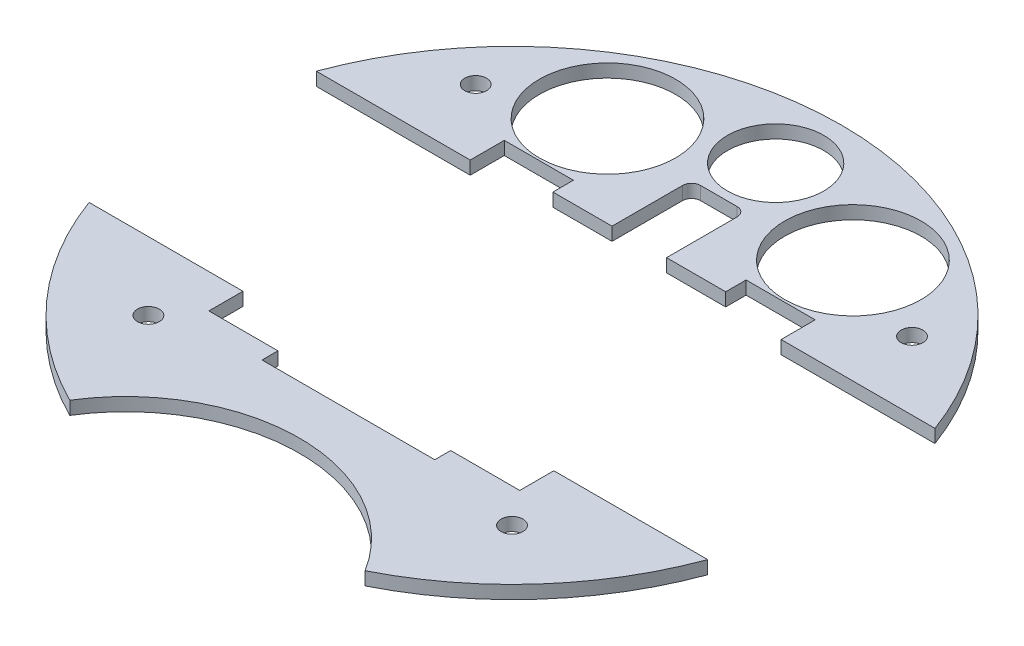
SolidWorks part; units mm, degrees
material "ABS"
ref_plane "Front Plane" through (0, 0, 0) normal (0, 0, 1) x (1, 0, 0)
ref_plane "Top Plane" through (0, 0, 0) normal (0, 1, 0) x (1, 0, 0)
ref_plane "Right Plane" through (0, 0, 0) normal (1, 0, 0) x (0, 0, -1)
sketch "Sketch1" plane through (0, 0, 0) normal (0, 1, 0) x (1, 0, 0)
  line L0 (0, -85) -> (-32.4891, -64.8129) construction
  line L1 (0, -85) -> (0, 0) construction
  arc A0 (32.4891, -64.8129) -> (-32.4891, -64.8129) centre (0, 0) ccw
  arc A1 (32.4891, -64.8129) -> (-32.4891, -64.8129) centre (0, -85) ccw
  dimension "D1" = 145
  dimension "D2" = 76.5
  dimension "D3" = 85
extrude "Boss-Extrude1" add sketch "Sketch1" along normal blind 2.9
sketch "solenoid placement" plane through (0, 2.9, 0) normal (0, 1, 0) x (1, 0, 0)
  line L4 (-19, -36) -> (19, -36)
  line L5 (-19, 28) -> (-19, -36)
  line L10 (19, 28) -> (-19, 28)
  line L11 (19, -36) -> (19, 28)
  line L12 (-19, -36) -> (19, -36)
  line L13 (-19, 28) -> (-19, -36)
  line L14 (19, 28) -> (-19, 28)
  line L15 (19, -36) -> (19, 28)
  dimension "D1" = 0
extrude "Cut-Extrude1" cut sketch "solenoid placement" against normal through all
sketch "Sketch7" plane through (0, 2.9, 0) normal (0, 1, 0) x (1, 0, 0)
  circle A3 centre (27, 48) radius 15
  circle A4 centre (27, 48) radius 15
  circle A5 centre (-27, 48) radius 15
  circle A6 centre (-27, 48) radius 15
  dimension "D1" = 0
  dimension "D2" = 0
extrude "Cut-Extrude6" cut sketch "Sketch7" against normal through all
sketch "Sketch8" plane through (0, 2.9, 0) normal (0, 1, 0) x (1, 0, 0)
  circle A1 centre (40, -40) radius 2.4
  circle A2 centre (40, -40) radius 2.4
  circle A3 centre (-40, -40) radius 2.4
  circle A4 centre (-40, -40) radius 2.4
  circle A5 centre (48, 40) radius 2.4
  circle A6 centre (48, 40) radius 2.4
  circle A7 centre (-48, 40) radius 2.4
  circle A8 centre (-48, 40) radius 2.4
  dimension "D1" = 0
  dimension "D2" = 0
  dimension "D3" = 0
  dimension "D4" = 0
extrude "Cut-Extrude7" cut sketch "Sketch8" against normal through all
sketch "Sketch3" plane through (0, 2.9, 0) normal (0, 1, 0) x (1, 0, 0)
  line L1 (-34.2, -32.5) -> (-22.2, -32.5)
  line L2 (-34.2, 25) -> (-68.0533, 25)
  line L3 (-34.2, 32.5) -> (-22.2, 32.5)
  line L4 (-22.2, -32.5) -> (-22.2, 32.5) construction
  line L8 (0, 0) -> (0, 72.5) construction
  line L17 (-34.2, -32.5) -> (-34.2, -25)
  line L18 (-34.2, -25) -> (-68.0533, -25)
  line L19 (-34.2, 25) -> (-34.2, 32.5)
  line L21 (-22.2, 32.5) -> (-19, 32.5)
  line L22 (-22.2, 32.5) -> (-22.2, -32.5) construction
  line L23 (-22.2, -32.5) -> (-19, -32.5)
  line L24 (-19, 32.5) -> (-19, -32.5)
  line L25 (22.2, 32.5) -> (22.2, -32.5) construction
  line L26 (22.2, -32.5) -> (22.2, 32.5) construction
  line L27 (19, 32.5) -> (19, -32.5)
  line L28 (22.2, -32.5) -> (19, -32.5)
  line L29 (22.2, 32.5) -> (19, 32.5)
  line L30 (34.2, 25) -> (34.2, 32.5)
  line L31 (34.2, -25) -> (68.0533, -25)
  line L32 (34.2, -32.5) -> (34.2, -25)
  line L33 (34.2, 32.5) -> (22.2, 32.5)
  line L34 (34.2, 25) -> (68.0533, 25)
  line L35 (34.2, -32.5) -> (22.2, -32.5)
  line L36 (-19, 28) -> (-19, -36) construction
  arc A0 (32.4891, -64.8129) -> (-32.4891, -64.8129) centre (0, 0) ccw construction
  arc A2 (68.0533, 25) -> (68.0533, -25) centre (0, 0) cw
  arc A3 (-68.0533, 25) -> (-68.0533, -25) centre (0, 0) ccw
  point P31 (-34.2, -32.5)
  dimension "D1" = 50
extrude "Cut-Extrude3" cut sketch "Sketch3" against normal through all
sketch "Sketch9" plane through (0, 2.9, 0) normal (0, 1, 0) x (1, 0, 0)
  line L0 (6, 43.5) -> (6, 28)
  line L1 (-6, 43.5) -> (-6, 28)
  line L2 (19, 28) -> (-19, 28) construction
  line L8 (-6, 28) -> (6, 28)
  line L10 (4, 45.5) -> (-4, 45.5)
  arc A0 (-6, 43.5) -> (-4, 45.5) centre (-4, 43.5) cw
  arc A1 (6, 43.5) -> (4, 45.5) centre (4, 43.5) ccw
  point P5 (0, 28)
  point P6 (0, 28)
  point P16 (-6, 45.5)
  point P19 (6, 45.5)
  dimension "D3" = 2
  dimension "D2" = 12
  dimension "D1" = 17.5
extrude "Cut-Extrude8" cut sketch "Sketch9" against normal through all
sketch "Sketch10" plane through (0, 2.9, 0) normal (0, 1, 0) x (1, 0, 0)
  line L0 (0, 0) -> (0, 58) construction
  circle A0 centre (0, 58) radius 10.605
  dimension "D1" = 21.21
  dimension "D2" = 58
extrude "Cut-Extrude9" cut sketch "Sketch10" against normal through all
equation "\"smallPulleyTeeth\"= 15"
equation "\"largePulleyTeeth\"= 30"
equation "\"eighthThick\"= 2.9mm"
equation "\"sixteenthThick\" = 1.7mm"
equation "\"quarterThick\"=6.0mm"
equation "\"OD\" = 145mm"
equation "\"puckAngle\" = 60.5deg"
equation "\"D1@Sketch1\"=\"OD\""
equation "\"puckDiam\" = 76.5mm"
equation "\"D2@Sketch1\"=\"puckDiam\""
equation "\"D1@Boss-Extrude1\"=\"eighthThick\""
equation "\"axlePress\" = 5.9mm"
equation "\"press\" = 0.2mm"
equation "\"wheelClear\" = 0.3mm"
equation "\"10-32clear\" = 4.8mm"
equation "\"6-32clear\" = 3.3mm"
equation "\"8-32clear\" = 4.0mm"
equation "\"4-40clear\" = 3.0mm"
equation "\"wheelHeight\" = 22mm"
equation "\"wheelWell\" = 65mm"
equation "\"puckDist\" = 85mm"
equation "\"D3@Sketch1\"=\"puckDist\""
equation "\"scoopFillet\" = 5mm"
